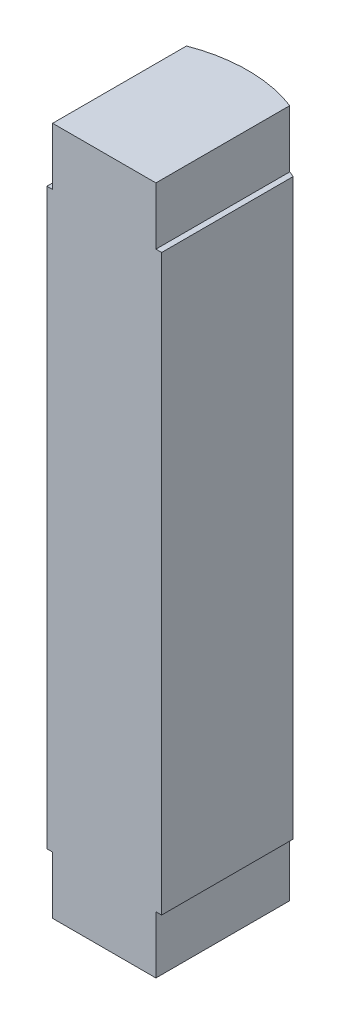
SolidWorks part; units mm, degrees
ref_plane "Front Plane" through (0, 0, 0) normal (0, 0, 1) x (1, 0, 0)
ref_plane "Top Plane" through (0, 0, 0) normal (0, 1, 0) x (1, 0, 0)
ref_plane "Right Plane" through (0, 0, 0) normal (1, 0, 0) x (0, 0, -1)
sketch "Sketch2" plane through (0, 0, 0) normal (0, 1, 0) x (1, 0, 0)
  line L0 (-5, 0) -> (5, 0)
  line L1 (5, 0) -> (5, 11.4564)
  line L3 (-5, 11.4564) -> (-5, 0)
  arc A0 (5, 11.4564) -> (-5, 11.4564) centre (0, 0) ccw
  dimension "D1" = 12.5
  dimension "D2" = 10
extrude "Boss-Extrude1" add sketch "Sketch2" along normal blind 60
sketch "Sketch3" plane through (0, 0, 0) normal (0, 0, 1) x (1, 0, 0)
  line L0 (0, 0) -> (0, 3.9559) construction
  line L1 (-5, 0) -> (-4.5, 0)
  line L2 (-5, 0) -> (-5, 5)
  line L3 (-5, 5) -> (-4.5, 5)
  line L4 (-4.5, 0) -> (-4.5, 5)
  line L5 (4.5, 0) -> (4.5, 5)
  line L6 (5, 5) -> (4.5, 5)
  line L7 (5, 0) -> (5, 5)
  line L8 (5, 0) -> (4.5, 0)
  line L9 (-5, 30) -> (5, 30) construction
  line L10 (-5, 60) -> (-5, 0) construction
  line L11 (5, 60) -> (5, 0) construction
  line L12 (5, 60) -> (4.5, 60)
  line L13 (5, 60) -> (5, 55)
  line L14 (5, 55) -> (4.5, 55)
  line L15 (4.5, 60) -> (4.5, 55)
  line L16 (-4.5, 60) -> (-4.5, 55)
  line L17 (-5, 55) -> (-4.5, 55)
  line L18 (-5, 60) -> (-5, 55)
  line L19 (-5, 60) -> (-4.5, 60)
  dimension "D1" = 5
  dimension "D2" = 0.5
extrude "Cut-Extrude1" cut sketch "Sketch3" against normal blind 20
